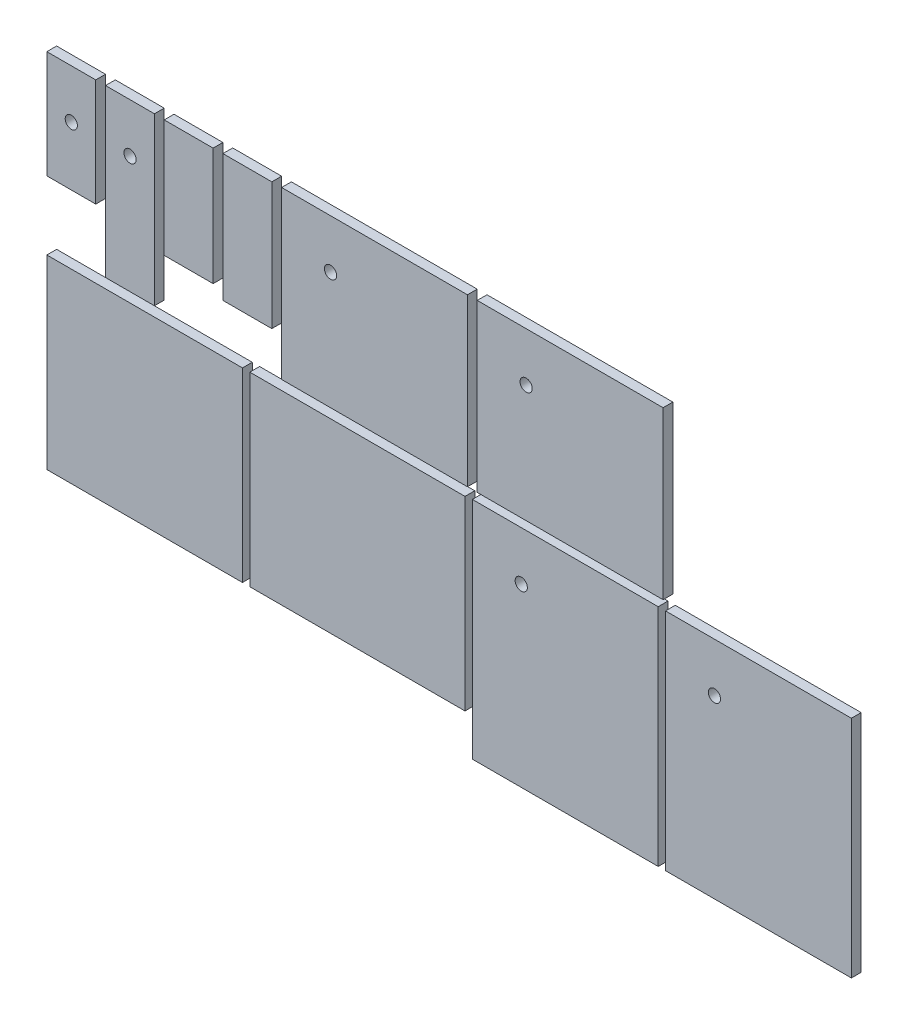
SolidWorks part; units mm, degrees
ref_plane "Front Plane" through (0, 0, 0) normal (0, 0, 1) x (1, 0, 0)
ref_plane "Top Plane" through (0, 0, 0) normal (0, 1, 0) x (1, 0, 0)
ref_plane "Right Plane" through (0, 0, 0) normal (1, 0, 0) x (0, 0, -1)
sketch "Sketch1" plane through (0, 0, 0) normal (0, 0, 1) x (1, 0, 0)
  line L1 (-53.2926, 57.9731) -> (-27.8926, 57.9731)
  line L2 (-53.2926, 57.9731) -> (-53.2926, 2.0931)
  line L3 (-53.2926, 2.0931) -> (-27.8926, 2.0931)
  line L4 (-27.8926, 57.9731) -> (-27.8926, 2.0931)
  line L5 (-22.8126, 57.9731) -> (2.5874, 57.9731)
  line L6 (-22.8126, 57.9731) -> (-22.8126, -28.3869)
  line L7 (-22.8126, -28.3869) -> (2.5874, -28.3869)
  line L8 (2.5874, 57.9731) -> (2.5874, -28.3869)
  line L9 (7.6674, 57.7707) -> (33.0674, 57.7707)
  line L10 (7.6674, 57.7707) -> (7.6674, -3.1893)
  line L11 (7.6674, -3.1893) -> (33.0674, -3.1893)
  line L12 (33.0674, 57.7707) -> (33.0674, -3.1893)
  line L13 (38.1474, 57.8498) -> (63.5474, 57.8498)
  line L14 (38.1474, 57.8498) -> (38.1474, -8.1902)
  line L15 (38.1474, -8.1902) -> (63.5474, -8.1902)
  line L16 (63.5474, 57.8498) -> (63.5474, -8.1902)
  line L17 (-53.2926, -33.4669) -> (48.3074, -33.4669)
  line L18 (-53.2926, -33.4669) -> (-53.2926, -129.9869)
  line L19 (-53.2926, -129.9869) -> (48.3074, -129.9869)
  line L20 (48.3074, -33.4669) -> (48.3074, -129.9869)
  line L21 (52.1174, -33.4669) -> (163.8774, -33.4669)
  line L22 (52.1174, -33.4669) -> (52.1174, -129.9869)
  line L23 (52.1174, -129.9869) -> (163.8774, -129.9869)
  line L24 (163.8774, -33.4669) -> (163.8774, -129.9869)
  line L25 (68.6274, 57.8498) -> (165.1474, 57.8498)
  line L26 (68.6274, 57.8498) -> (68.6274, -28.5102)
  line L27 (68.6274, -28.5102) -> (165.1474, -28.5102)
  line L28 (165.1474, 57.8498) -> (165.1474, -28.5102)
  line L29 (170.2274, 57.8498) -> (266.7474, 57.8498)
  line L30 (170.2274, 57.8498) -> (170.2274, -28.5102)
  line L31 (170.2274, -28.5102) -> (266.7474, -28.5102)
  line L32 (266.7474, 57.8498) -> (266.7474, -28.5102)
  line L33 (167.6874, -32.9096) -> (264.2074, -32.9096)
  line L34 (167.6874, -32.9096) -> (167.6874, -149.7496)
  line L35 (167.6874, -149.7496) -> (264.2074, -149.7496)
  line L36 (264.2074, -32.9096) -> (264.2074, -149.7496)
  line L37 (268.0174, -32.9096) -> (364.5374, -32.9096)
  line L38 (268.0174, -32.9096) -> (268.0174, -149.7496)
  line L39 (268.0174, -149.7496) -> (364.5374, -149.7496)
  line L40 (364.5374, -32.9096) -> (364.5374, -149.7496)
  circle A0 centre (-40.5926, 32.5731) radius 3.175
  circle A1 centre (-10.1126, 32.5731) radius 3.175
  circle A2 centre (94.0274, 32.4498) radius 3.175
  circle A3 centre (195.6274, 32.4498) radius 3.175
  circle A4 centre (193.0874, -58.3096) radius 3.175
  circle A5 centre (293.4174, -58.3096) radius 3.175
  dimension "D8" = 6.35
  dimension "D9" = 6.35
  dimension "D28" = 6.35
  dimension "D34" = 6.35
  dimension "D43" = 6.35
  dimension "D44" = 6.35
  dimension "D1" = 25.4
  dimension "D2" = 55.88
  dimension "D3" = 25.4
  dimension "D4" = 86.36
  dimension "D5" = 5.08
  dimension "D6" = 12.7
  dimension "D7" = 12.7
  dimension "D10" = 25.4
  dimension "D11" = 25.4
  dimension "D12" = 60.96
  dimension "D13" = 25.4
  dimension "D14" = 5.08
  dimension "D15" = 66.04
  dimension "D16" = 25.4
  dimension "D17" = 5.08
  dimension "D18" = 96.52
  dimension "D19" = 101.6
  dimension "D20" = 25.4
  dimension "D21" = 5.08
  dimension "D22" = 96.52
  dimension "D23" = 111.76
  dimension "D24" = 3.81
  dimension "D25" = 96.52
  dimension "D26" = 86.36
  dimension "D27" = 5.08
  dimension "D29" = 25.4
  dimension "D30" = 25.4
  dimension "D31" = 96.52
  dimension "D32" = 86.36
  dimension "D33" = 5.08
  dimension "D35" = 25.4
  dimension "D36" = 25.4
  dimension "D37" = 116.84
  dimension "D38" = 96.52
  dimension "D39" = 3.81
  dimension "D40" = 5.08
  dimension "D41" = 96.52
  dimension "D42" = 116.84
  dimension "D45" = 25.4
  dimension "D46" = 25.4
  dimension "D47" = 25.4
  dimension "D48" = 25.4
  dimension "D49" = 3.81
extrude "Boss-Extrude1" add sketch "Sketch1" along normal blind 5.08
